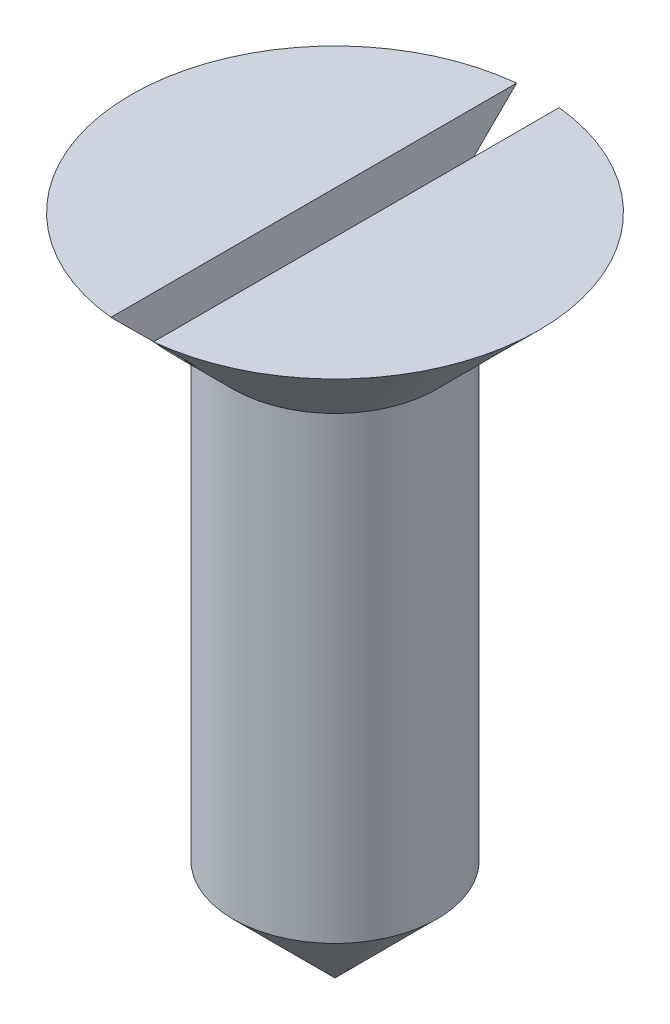
SolidWorks part; units mm, degrees
ref_plane "Front Plane" through (0, 0, 0) normal (0, 0, 1) x (1, 0, 0)
ref_plane "Top Plane" through (0, 0, 0) normal (0, 1, 0) x (1, 0, 0)
ref_plane "Right Plane" through (0, 0, 0) normal (1, 0, 0) x (0, 0, -1)
sketch "Sketch1" plane through (0, 0, 0) normal (1, 0, 0) x (0, 0, -1)
  line L0 (0, 0) -> (6, 6)
  line L1 (6, 6) -> (6, 33)
  line L2 (6, 33) -> (12, 39)
  line L3 (12, 39) -> (0, 39)
  line L4 (0, 39) -> (0, 0)
  line L5 (6, 33) -> (33.5389, 33) construction
  dimension "D1" = 6
  dimension "D2" = 27
  dimension "D3" = 6
  dimension "D4" = 12
  dimension "D5" = 135
revolve "Revolve1" add sketch "Sketch1" angle 360 about L4
sketch "Sketch2" plane through (0, 0, 0) normal (0, 0, 1) x (1, 0, 0)
  line L0 (0, 0) -> (0, 47.9506) construction
  line L1 (-1.25, 39) -> (1.25, 39)
  line L2 (-1.25, 39) -> (-1.25, 36.5)
  line L3 (-1.25, 36.5) -> (1.25, 36.5)
  line L4 (1.25, 39) -> (1.25, 36.5)
  line L5 (12, 39) -> (-12, 39) construction
  dimension "D1" = 2.5
  dimension "D2" = 2.5
extrude "Cut-Extrude1" cut sketch "Sketch2" against normal through all both and the other way through all
